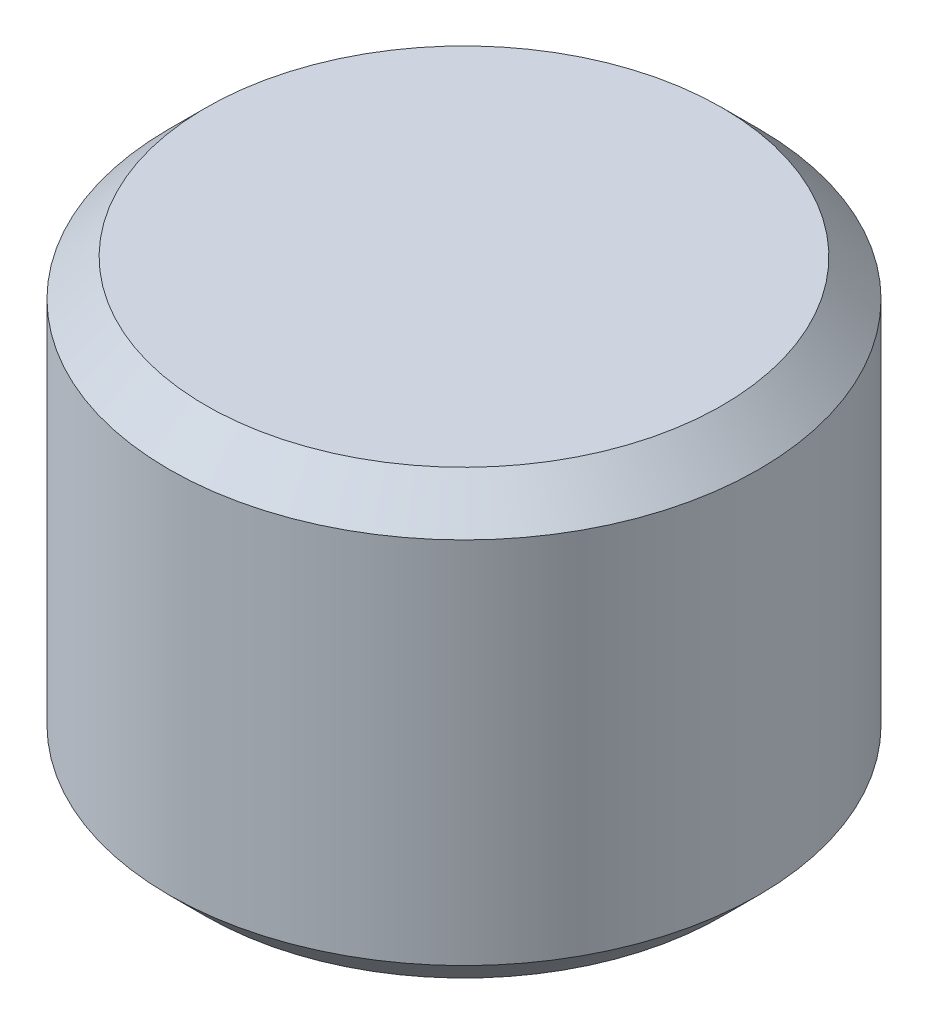
SolidWorks part; units mm, degrees
material "acero"
ref_plane "Alzado" through (0, 0, 0) normal (0, 0, 1) x (1, 0, 0)
ref_plane "Planta" through (0, 0, 0) normal (0, 1, 0) x (1, 0, 0)
ref_plane "Vista lateral" through (0, 0, 0) normal (1, 0, 0) x (0, 0, -1)
sketch "Croquis1" plane through (0, 0, 0) normal (0, 0, 1) x (1, 0, 0)
  line L0 (0, 0) -> (0, -60.9498) construction
  line L3 (0, 0) -> (4, 0)
  line L4 (4, 0) -> (4, -6)
  line L5 (4, -6) -> (0, -6)
  line L6 (0, -6) -> (0, 0)
  dimension "D1" = 6
  dimension "D4" = 8
revolve "Revolución1" add sketch "Croquis1" angle 360 about L0
chamfer "Chaflán1" distance 0.5 angle 45 2 edges at (0, -6, 4) (0, 0, 4)
sketch "Croquis2" plane through (0, -6, 0) normal (0, -1, 0) x (1, 0, 0)
  line L1 (-1.1547, -2) -> (1.1547, -2)
  line L2 (1.1547, -2) -> (2.3094, 0)
  line L3 (2.3094, 0) -> (1.1547, 2)
  line L4 (1.1547, 2) -> (-1.1547, 2)
  line L5 (-1.1547, 2) -> (-2.3094, 0)
  line L6 (-2.3094, 0) -> (-1.1547, -2)
  circle A0 centre (0, 0) radius 2 construction
  dimension "D1" = 4
extrude "Cortar-Extruir1" cut sketch "Croquis2" against normal blind 4
